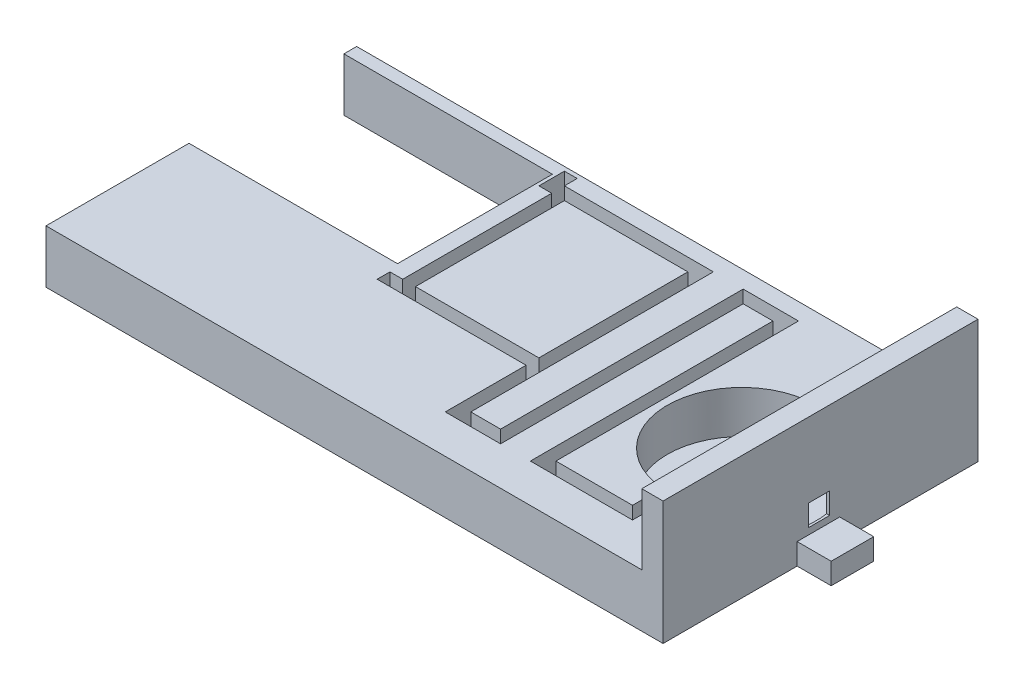
SolidWorks part; units mm, degrees
ref_plane "Front Plane" through (0, 0, 0) normal (0, 0, 1) x (1, 0, 0)
ref_plane "Top Plane" through (0, 0, 0) normal (0, 1, 0) x (1, 0, 0)
ref_plane "Right Plane" through (0, 0, 0) normal (1, 0, 0) x (0, 0, -1)
sketch "Sketch1" plane through (0, 0, 0) normal (0, 1, 0) x (1, 0, 0)
  line L0 (-38.4661, 17.625) -> (-38.4661, -55.375)
  line L1 (-63.4661, 17.625) -> (81.5339, 17.625)
  line L2 (-63.4661, 17.625) -> (-63.4661, -55.375)
  line L3 (-63.4661, -55.375) -> (81.5339, -55.375)
  line L4 (81.5339, 17.625) -> (81.5339, -55.375)
  line L5 (-38.4661, 5.6853) -> (81.5339, 5.6853)
  dimension "D1" = 73
  dimension "D2" = 145
  dimension "D3" = 120
extrude "Boss-Extrude1" add sketch "Sketch1" along normal blind 12.5 contours L2 L1 L4 L3
sketch "Sketch2" plane through (0, 12.5, 0) normal (0, 1, 0) x (1, 0, 0)
  line L0 (63.5339, -18.875) -> (81.5339, -18.875)
  line L1 (81.5339, 17.625) -> (81.5339, -55.375) construction
  line L3 (63.5339, -18.875) -> (63.5339, 17.625)
  line L4 (-63.4661, 17.625) -> (81.5339, 17.625) construction
  circle A0 centre (63.5339, -18.875) radius 17.5
  dimension "D1" = 35
  dimension "D2" = 18
  dimension "D3" = 36.5
extrude "Cut-Extrude1" cut sketch "Sketch2" against normal blind 10 contours A0
sketch "Sketch3" plane through (81.5339, 0, 0) normal (1, 0, 0) x (0, 0, -1)
  line L1 (-21.2217, 11.5) -> (-16.2217, 11.5)
  line L2 (-21.2217, 11.5) -> (-21.2217, 6.5)
  line L3 (-21.2217, 6.5) -> (-16.2217, 6.5)
  line L4 (-16.2217, 11.5) -> (-16.2217, 6.5)
  dimension "D1" = 5
  dimension "D2" = 5
extrude "Cut-Extrude2" cut sketch "Sketch3" against normal blind 10 contours L2 L1 L4 L3
sketch "Sketch4" plane through (81.5339, 0, 0) normal (1, 0, 0) x (0, 0, -1)
  line L0 (17.625, 0) -> (-55.375, 0) construction
  line L1 (-23.875, 5) -> (-13.875, 5)
  line L2 (-23.875, 5) -> (-23.875, 0)
  line L3 (-23.875, 0) -> (-13.875, 0)
  line L4 (-13.875, 5) -> (-13.875, 0)
  line L8 (-55.375, 12.5) -> (-55.375, 0) construction
  line L9 (-55.375, 5) -> (-23.875, 5)
  dimension "D1" = 10
  dimension "D2" = 5
  dimension "D3" = 31.5
extrude "Boss-Extrude2" add sketch "Sketch4" along normal blind 8 contours L2 L1 L4 L3
sketch "Sketch6" plane through (0, 12.5, 0) normal (0, 1, 0) x (1, 0, 0)
  line L0 (-63.4661, -55.375) -> (81.5339, -55.375) construction
  line L1 (81.5339, 17.625) -> (76.5339, 17.625)
  line L2 (81.5339, 17.625) -> (81.5339, -55.375)
  line L3 (81.5339, -55.375) -> (76.5339, -55.375)
  line L4 (76.5339, 17.625) -> (76.5339, -55.375)
  dimension "D1" = 5
extrude "Boss-Extrude3" add sketch "Sketch6" along normal blind 15.5 contours L2 L1 L4 L3
sketch "Sketch7" plane through (0, 12.5, 0) normal (0, 1, 0) x (1, 0, 0)
  line L0 (76.5339, 14.625) -> (-14.4661, 14.625)
  line L1 (76.5339, 17.625) -> (76.5339, -7.1597) construction
  line L2 (-14.4661, 14.625) -> (-14.4661, -55.375)
  line L3 (-63.4661, -55.375) -> (76.5339, -55.375) construction
  line L4 (-0.7874, 17.625) -> (-0.7874, 14.625)
  line L5 (-63.4661, 17.625) -> (76.5339, 17.625) construction
  line L6 (-63.4661, 17.625) -> (-63.4661, -55.375) construction
  line L7 (-14.4661, 14.625) -> (-63.4661, 14.625)
  line L8 (-14.4661, 14.625) -> (-14.4661, -21.775)
  line L9 (-14.4661, -21.775) -> (-63.4661, -21.775)
  line L10 (-63.4661, 14.625) -> (-63.4661, -21.775)
  dimension "D1" = 91
  dimension "D2" = 3
  dimension "D3" = 36.4
extrude "Cut-Extrude5" cut sketch "Sketch7" against normal blind 15.5 contours L8 L7 L10 L9
sketch "Sketch8" plane through (0, 12.5, 0) normal (0, 1, 0) x (1, 0, 0)
  line L1 (62.3085, -36.3321) -> (65.3085, -36.3321)
  line L2 (62.3085, -36.3321) -> (62.3085, -43.3321)
  line L3 (62.3085, -46.3321) -> (65.3085, -46.3321)
  line L4 (65.3085, -36.3321) -> (65.3085, -46.3321)
  line L5 (62.3085, -46.3321) -> (41.3085, -46.3321)
  line L7 (62.3085, -43.3321) -> (44.3085, -43.3321)
  line L8 (41.3085, -46.3321) -> (41.3085, -43.3321)
  line L10 (41.3085, -43.3321) -> (41.3085, 10.6679)
  line L11 (41.3085, 13.6679) -> (44.3085, 13.6679)
  line L12 (44.3085, -43.3321) -> (44.3085, 13.6679)
  line L13 (41.3085, 13.6679) -> (31.3085, 13.6679)
  line L15 (41.3085, 10.6679) -> (34.3085, 10.6679)
  line L16 (31.3085, 13.6679) -> (31.3085, 10.6679)
  line L18 (31.3085, 10.6679) -> (31.3085, -43.3321)
  line L19 (31.3085, -46.3321) -> (34.3085, -46.3321)
  line L20 (34.3085, 10.6679) -> (34.3085, -46.3321)
  line L21 (31.3085, -46.3321) -> (21.3085, -46.3321)
  line L23 (31.3085, -43.3321) -> (24.3085, -43.3321)
  line L24 (21.3085, -46.3321) -> (21.3085, -43.3321)
  line L26 (21.3085, -43.3321) -> (21.3085, -27.3321)
  line L27 (21.3085, 13.6679) -> (24.3085, 13.6679)
  line L28 (24.3085, -43.3321) -> (24.3085, 13.6679)
  line L29 (21.3085, 13.6679) -> (-10.6915, 13.6679)
  line L31 (21.3085, 10.6679) -> (-7.6915, 10.6679)
  line L32 (-13.6915, 13.6679) -> (-13.6915, 10.6679)
  line L33 (21.3085, -24.3321) -> (-7.6915, -24.3321)
  line L34 (24.3085, -24.3321) -> (24.3085, -27.3321)
  line L35 (21.3085, -27.3321) -> (-13.6915, -27.3321)
  line L36 (-13.6915, -24.3321) -> (-13.6915, -27.3321)
  line L37 (-10.6915, -24.3321) -> (-13.6915, -24.3321)
  line L39 (-13.6915, 13.6679) -> (-13.6915, 16.6679)
  line L40 (-13.6915, 16.6679) -> (-10.6915, 16.6679)
  line L41 (-10.6915, 13.6679) -> (-10.6915, 16.6679)
  line L42 (-10.6915, 13.6679) -> (-7.6915, 13.6679)
  line L43 (-10.6915, 10.6679) -> (-10.6915, -24.3321)
  line L45 (-7.6915, 10.6679) -> (-7.6915, -24.3321)
  line L46 (-10.6915, 10.6679) -> (-13.6915, 10.6679)
  line L47 (21.3085, -24.3321) -> (21.3085, 10.6679)
  arc A0 (76.5339, -7.1597) -> (76.5339, -30.5904) centre (63.5339, -18.875) ccw construction
  dimension "D1" = 10
  dimension "D2" = 3
  dimension "D3" = 21
  dimension "D4" = 3
  dimension "D5" = 57
  dimension "D6" = 3
  dimension "D7" = 10
  dimension "D8" = 3
  dimension "D9" = 3
  dimension "D10" = 57
  dimension "D11" = 3
  dimension "D12" = 10
  dimension "D13" = 3
  dimension "D14" = 35
  dimension "D15" = 3
  dimension "D17" = 3
  dimension "D18" = 3
  dimension "D19" = 3
extrude "Cut-Extrude7" cut sketch "Sketch8" against normal blind 10
sketch "Sketch9" plane through (0, 2.5, 0) normal (0, 1, 0) x (1, 0, 0)
  line L0 (1.2142, 13.6679) -> (1.2142, 10.6679)
  line L1 (-7.6915, 10.6679) -> (21.3085, 10.6679)
  line L2 (-7.6915, 10.6679) -> (-7.6915, -24.3321)
  line L3 (-7.6915, -24.3321) -> (21.3085, -24.3321)
  line L4 (21.3085, 10.6679) -> (21.3085, -24.3321)
  line L5 (-10.6915, 13.6679) -> (24.3085, 13.6679) construction
  line L6 (-10.6915, 7.1595) -> (-7.6915, 7.1595)
  line L7 (-10.6915, 10.6679) -> (-10.6915, -24.3321) construction
  line L8 (21.3085, -0.9427) -> (24.3085, -0.9427)
  line L9 (24.3085, -43.3321) -> (24.3085, 13.6679) construction
  dimension "D1" = 3
  dimension "D2" = 3
  dimension "D3" = 29
  dimension "D4" = 35
  dimension "D5" = 3
extrude "Boss-Extrude4" add sketch "Sketch9" along normal blind 10 contours L2 L1 L4 L3
sketch "Sketch12" plane through (0, 28, 0) normal (0, 1, 0) x (1, 0, 0)
  line L1 (76.5339, 17.625) -> (81.5339, 17.625)
  line L2 (76.5339, 17.625) -> (76.5339, 18.625)
  line L3 (76.5339, 18.625) -> (81.5339, 18.625)
  line L4 (81.5339, 17.625) -> (81.5339, 18.625)
  dimension "D1" = 5
  dimension "D2" = 1
extrude "Boss-Extrude17" add sketch "Sketch12" against normal up to vertex (28 mm away)
sketch "Sketch13" plane through (0, 28, 0) normal (0, 1, 0) x (1, 0, 0)
  line L0 (81.5339, -55.375) -> (76.5339, -55.375) construction
  line L1 (76.5339, 18.625) -> (81.5339, 18.625)
  line L2 (76.5339, 18.625) -> (76.5339, -55.375)
  line L3 (76.5339, -55.375) -> (81.5339, -55.375)
  line L4 (81.5339, 18.625) -> (81.5339, -55.375)
  line L5 (81.5339, 18.625) -> (81.5339, -55.375) construction
extrude "Boss-Extrude18" add sketch "Sketch13" along normal blind 1
sketch "Sketch15" plane through (0, 2.5, 0) normal (0, 1, 0) x (1, 0, 0)
  line L0 (81.5339, -23.875) -> (81.5339, -13.875) construction
  line L1 (57.223, -11.4807) -> (71.0117, -11.4807)
  line L2 (57.223, -11.4807) -> (57.223, -24.9437)
  line L3 (57.223, -24.9437) -> (71.0117, -24.9437)
  line L4 (71.0117, -11.4807) -> (71.0117, -24.9437)
